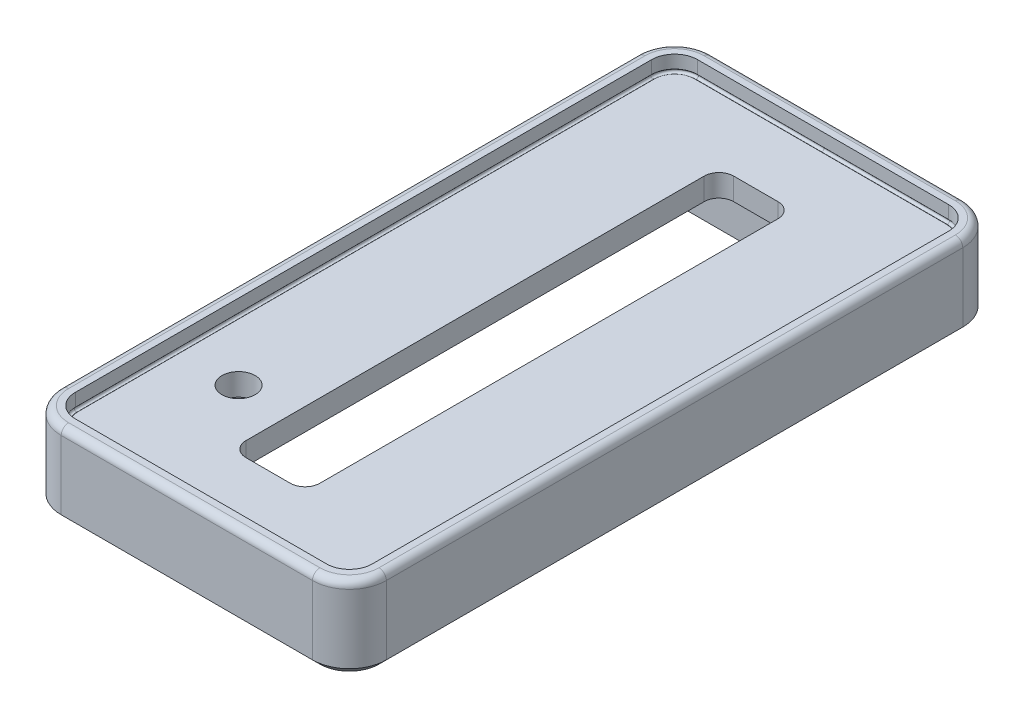
SolidWorks part; units mm, degrees
material "EN8"
ref_plane "Front Plane" through (0, 0, 0) normal (0, 0, 1) x (1, 0, 0)
ref_plane "Top Plane" through (0, 0, 0) normal (0, 1, 0) x (1, 0, 0)
ref_plane "Right Plane" through (0, 0, 0) normal (1, 0, 0) x (0, 0, -1)
sketch "Sketch1" plane through (0, 0, 0) normal (0, 1, 0) x (1, 0, 0)
  line L1 (-17, -44) -> (17, -44)
  line L2 (-22, -39) -> (-22, 39)
  line L3 (-17, 44) -> (17, 44)
  line L4 (22, -39) -> (22, 39)
  line L5 (-22, -44) -> (22, 44) construction
  line L6 (-22, 44) -> (22, -44) construction
  line L7 (16, -35) -> (-16, -35) construction
  line L8 (16, -35) -> (16, 35) construction
  line L9 (16, 35) -> (-16, 35) construction
  line L10 (-16, -35) -> (-16, 35) construction
  line L11 (16, -35) -> (-16, 35) construction
  line L12 (16, 35) -> (-16, -35) construction
  arc A0 (-17, -44) -> (-22, -39) centre (-17, -39) cw
  arc A1 (17, -44) -> (22, -39) centre (17, -39) ccw
  arc A2 (17, 44) -> (22, 39) centre (17, 39) cw
  arc A3 (-22, 39) -> (-17, 44) centre (-17, 39) cw
  point P0 (0, 0)
  point P18 (0, 0)
  dimension "D1" = 5
  dimension "D2" = 9
  dimension "D3" = 32
  dimension "D4" = 70
  dimension "D5" = 6
extrude "Boss-Extrude1" add sketch "Sketch1" along normal blind 9.2
ref_plane "Plane1" through (0, 1, 0) normal (0, 1, 0) x (1, 0, 0)
ref_plane "Plane2" through (0, 6.2, 0) normal (0, 1, 0) x (1, 0, 0)
sketch "Sketch4" plane through (0, 6.2, 0) normal (0, -1, 0) x (-1, 0, 0)
  line L0 (-16, -32) -> (-16, 32)
  line L1 (-13, -35) -> (13, -35) construction
  line L2 (-16, -32) -> (-16, 32) construction
  line L3 (-13, 35) -> (13, 35) construction
  line L4 (16, -32) -> (16, 32) construction
  line L5 (-16, -35) -> (16, 35) construction
  line L6 (-16, 35) -> (16, -35) construction
  line L7 (-13, 35) -> (13, 35)
  line L8 (16, -32) -> (16, 32)
  line L9 (-13, -35) -> (13, -35)
  arc A0 (-13, -35) -> (-16, -32) centre (-13, -32) cw construction
  arc A1 (13, -35) -> (16, -32) centre (13, -32) ccw construction
  arc A2 (13, 35) -> (16, 32) centre (13, 32) cw construction
  arc A3 (-16, 32) -> (-13, 35) centre (-13, 32) cw construction
  arc A4 (-16, 32) -> (-13, 35) centre (-13, 32) cw
  arc A5 (13, 35) -> (16, 32) centre (13, 32) cw
  arc A6 (13, -35) -> (16, -32) centre (13, -32) ccw
  arc A7 (-13, -35) -> (-16, -32) centre (-13, -32) cw
  point P0 (0, 0)
  dimension "D3" = 3
  dimension "D1" = 32
  dimension "D2" = 70
  dimension "D4" = 0
extrude "Cut-Extrude3" cut sketch "Sketch4" along normal through all
sketch "Sketch19" plane through (0, 6.2, 0) normal (0, -1, 0) x (1, 0, 0)
  line L1 (14.5739, -18.7366) -> (-14.5739, -18.7366) construction
  line L2 (14.5739, -18.7366) -> (14.5739, 18.7366) construction
  line L3 (14.5739, 18.7366) -> (-14.5739, 18.7366) construction
  line L4 (-14.5739, -18.7366) -> (-14.5739, 18.7366) construction
  line L5 (14.5739, -18.7366) -> (-14.5739, 18.7366) construction
  line L6 (14.5739, 18.7366) -> (-14.5739, -18.7366) construction
  circle A1 centre (-14.5739, 18.7366) radius 1
  circle A2 centre (14.5739, 18.7366) radius 1
  circle A3 centre (14.5739, -18.7366) radius 1
  circle A4 centre (-14.5739, -18.7366) radius 1
  point P0 (0, 0)
  dimension "D1" = 2
sketch "Sketch18" plane through (0, 6.2, 0) normal (0, -1, 0) x (1, 0, 0)
  line L0 (13, 35) -> (-13, 35) construction
  line L1 (-3, -33) -> (3, -33)
  line L2 (-5, -31) -> (-5, 31)
  line L3 (-3, 33) -> (3, 33)
  line L4 (5, -31) -> (5, 31)
  line L5 (-5, -33) -> (5, 33) construction
  line L6 (-5, 33) -> (5, -33) construction
  arc A0 (-3, -33) -> (-5, -31) centre (-3, -31) cw
  arc A1 (3, -33) -> (5, -31) centre (3, -31) ccw
  arc A2 (5, 31) -> (3, 33) centre (3, 31) ccw
  arc A3 (-5, 31) -> (-3, 33) centre (-3, 31) cw
  circle A4 centre (-12, 25) radius 2.25
  point P0 (0, 0)
  dimension "D3" = 2
  dimension "D4" = 25
  dimension "D5" = 12
  dimension "D6" = 4.5
  dimension "D1" = 10
  dimension "D2" = 2
extrude "Cut-Extrude10" cut sketch "Sketch18" against normal blind 10
sketch "Sketch9" plane through (0, 9.2, 0) normal (0, 1, 0) x (1, 0, 0)
  line L8 (-17, -42) -> (17, -42)
  line L9 (20, -39) -> (20, 39)
  line L10 (-20, 39) -> (-20, -39)
  line L11 (17, 42) -> (-17, 42)
  line L12 (-17, -42) -> (17, -42)
  line L13 (20, -39) -> (20, 39)
  line L14 (-20, 39) -> (-20, -39)
  line L15 (17, 42) -> (-17, 42)
  line L16 (-17, -44) -> (17, -44)
  line L17 (22, -39) -> (22, 39)
  line L18 (17, 44) -> (-17, 44)
  line L19 (-22, 39) -> (-22, -39)
  line L20 (-17, -44) -> (17, -44)
  line L21 (22, -39) -> (22, 39)
  line L22 (17, 44) -> (-17, 44)
  line L23 (-22, 39) -> (-22, -39)
  arc A8 (-20, -39) -> (-17, -42) centre (-17, -39) ccw
  arc A9 (17, -42) -> (20, -39) centre (17, -39) ccw
  arc A10 (20, 39) -> (17, 42) centre (17, 39) ccw
  arc A11 (-17, 42) -> (-20, 39) centre (-17, 39) ccw
  arc A12 (-20, -39) -> (-17, -42) centre (-17, -39) ccw
  arc A13 (17, -42) -> (20, -39) centre (17, -39) ccw
  arc A14 (20, 39) -> (17, 42) centre (17, 39) ccw
  arc A15 (-17, 42) -> (-20, 39) centre (-17, 39) ccw
  arc A16 (-22, -39) -> (-17, -44) centre (-17, -39) ccw
  arc A17 (17, -44) -> (22, -39) centre (17, -39) ccw
  arc A18 (22, 39) -> (17, 44) centre (17, 39) ccw
  arc A19 (-17, 44) -> (-22, 39) centre (-17, 39) ccw
  arc A20 (-22, -39) -> (-17, -44) centre (-17, -39) ccw
  arc A21 (17, -44) -> (22, -39) centre (17, -39) ccw
  arc A22 (22, 39) -> (17, 44) centre (17, 39) ccw
  arc A23 (-17, 44) -> (-22, 39) centre (-17, 39) ccw
  dimension "D1" = 2
  dimension "D2" = 0
extrude "Boss-Extrude3" add sketch "Sketch9" along normal blind 2.1
fillet "Fillet3" radius 1 8 edges at (22, 11.3, 0) (20.5355, 11.3, 42.5355) (0, 11.3, 44) (-20.5355, 11.3, 42.5355) (-22, 11.3, 0) (-20.5355, 11.3, -42.5355) (0, 11.3, -44) (20.5355, 11.3, -42.5355)
sketch "Sketch12" plane through (0, 9.2, 0) normal (0, 1, 0) x (1, 0, 0)
  line L0 (-20.1, 39) -> (-20.1, -39)
  line L1 (-17, -42.1) -> (17, -42.1)
  line L2 (20.1, -39) -> (20.1, 39)
  line L3 (17, 42.1) -> (-17, 42.1)
  line L4 (-20, 39) -> (-20, -39)
  line L5 (-17, -42) -> (17, -42)
  line L6 (20, -39) -> (20, 39)
  line L7 (17, 42) -> (-17, 42)
  line L8 (-20, 39) -> (-20, -39)
  line L9 (-17, -42) -> (17, -42)
  line L10 (20, -39) -> (20, 39)
  line L11 (17, 42) -> (-17, 42)
  arc A0 (-20.1, -39) -> (-17, -42.1) centre (-17, -39) ccw
  arc A1 (17, -42.1) -> (20.1, -39) centre (17, -39) ccw
  arc A2 (20.1, 39) -> (17, 42.1) centre (17, 39) ccw
  arc A3 (-17, 42.1) -> (-20.1, 39) centre (-17, 39) ccw
  arc A4 (-20, -39) -> (-17, -42) centre (-17, -39) ccw
  arc A5 (17, -42) -> (20, -39) centre (17, -39) ccw
  arc A6 (20, 39) -> (17, 42) centre (17, 39) ccw
  arc A7 (-17, 42) -> (-20, 39) centre (-17, 39) ccw
  arc A8 (-20, -39) -> (-17, -42) centre (-17, -39) ccw
  arc A9 (17, -42) -> (20, -39) centre (17, -39) ccw
  arc A10 (20, 39) -> (17, 42) centre (17, 39) ccw
  arc A11 (-17, 42) -> (-20, 39) centre (-17, 39) ccw
  dimension "D1" = 0
  dimension "D2" = 0.1
extrude "Cut-Extrude8" cut sketch "Sketch12" along normal through all
sketch "Sketch13" plane through (0, 0, 0) normal (1, 0, 0) x (0, 0, -1)
  line L0 (36.1672, 9.2) -> (42.1, 9.2) construction
  line L2 (42.1, 9.2) -> (42.1, 9.966) construction
  line L3 (42.1, 11.3) -> (42.1, 9.2) construction
  line L4 (-31, 9.2) -> (31, 9.2) construction
  line L5 (42.1, 9.2) -> (41.9586, 9.3414) construction
  circle A1 centre (41.9586, 9.3414) radius 0.25
  dimension "D1" = 45
  dimension "D2" = 0.5
  dimension "D3" = 0.2
sketch "Sketch14" plane through (0, 9.2, 0) normal (0, 1, 0) x (1, 0, 0)
  line L4 (-20.1, 39) -> (-20.1, -39)
  line L5 (-17, -42.1) -> (17, -42.1)
  line L6 (20.1, -39) -> (20.1, 39)
  line L7 (17, 42.1) -> (-17, 42.1)
  line L8 (-20.1, 39) -> (-20.1, -39)
  line L9 (-17, -42.1) -> (17, -42.1)
  line L10 (20.1, -39) -> (20.1, 39)
  line L11 (17, 42.1) -> (-17, 42.1)
  arc A4 (-17, 42.1) -> (-20.1, 39) centre (-17, 39) ccw
  arc A5 (-20.1, -39) -> (-17, -42.1) centre (-17, -39) ccw
  arc A6 (17, -42.1) -> (20.1, -39) centre (17, -39) ccw
  arc A7 (20.1, 39) -> (17, 42.1) centre (17, 39) ccw
  arc A8 (-17, 42.1) -> (-20.1, 39) centre (-17, 39) ccw
  arc A9 (-20.1, -39) -> (-17, -42.1) centre (-17, -39) ccw
  arc A10 (17, -42.1) -> (20.1, -39) centre (17, -39) ccw
  arc A11 (20.1, 39) -> (17, 42.1) centre (17, 39) ccw
  dimension "D1" = 0
sweep "Cut-Sweep1" cut profiles "Sketch13" path "Sketch14"
sketch "Sketch17" plane through (0, 0, 0) normal (0, -1, 0) x (1, 0, 0)
  line L0 (17, 44) -> (-17, 44) construction
  line L1 (16, -38) -> (-16, -38) construction
  line L2 (16, -38) -> (16, 38) construction
  line L3 (16, 38) -> (-16, 38) construction
  line L4 (-16, -38) -> (-16, 38) construction
  line L5 (16, -38) -> (-16, 38) construction
  line L6 (16, 38) -> (-16, -38) construction
  line L7 (22, -39) -> (22, 39) construction
  circle A0 centre (-16, 38) radius 3.085
  circle A1 centre (16, 38) radius 3.085
  circle A2 centre (16, -38) radius 3.085
  circle A3 centre (-16, -38) radius 3.085
  point P0 (0, 0)
  dimension "D1" = 6.17
  dimension "D2" = 6
  dimension "D3" = 6
extrude "Cut-Extrude9" cut sketch "Sketch17" against normal blind 8.2
chamfer "Chamfer1" distance 1 angle 45 8 edges at (22, 0, 0) (20.5355, 0, -42.5355) (20.5355, 0, 42.5355) (0, 0, -44) (0, 0, 44) (-20.5355, 0, -42.5355) (-20.5355, 0, 42.5355) (-22, 0, 0)
